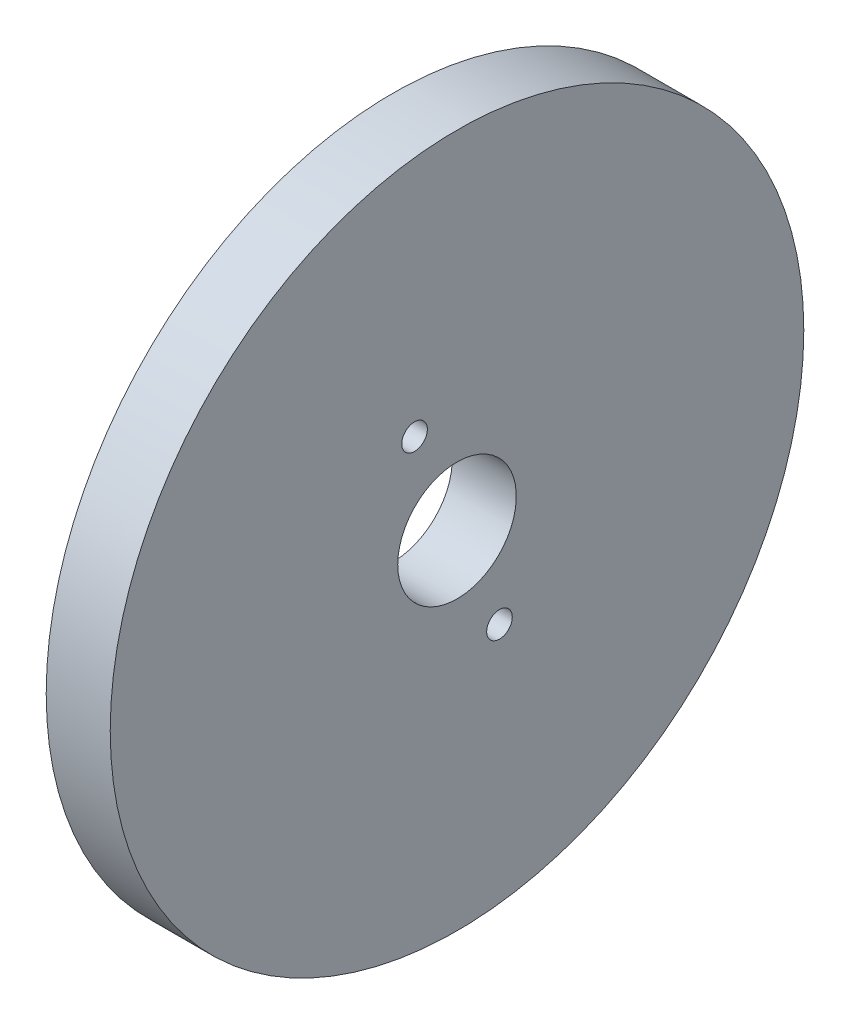
SolidWorks part; units mm, degrees
ref_plane "Front Plane" through (0, 0, 0) normal (0, 0, 1) x (1, 0, 0)
ref_plane "Top Plane" through (0, 0, 0) normal (0, 1, 0) x (1, 0, 0)
ref_plane "Right Plane" through (0, 0, 0) normal (1, 0, 0) x (0, 0, -1)
sketch "Axial profile (mm)" plane through (0, 0, 0) normal (0, 0, 1) x (1, 0, 0)
  line L0 (-110, 0) -> (75, 0) construction
  line L1 (13.7, 11.1125) -> (25.7, 11.1125)
  line L2 (25.7, 11.1125) -> (25.7, 65)
  line L3 (25.7, 65) -> (13.7, 65)
  line L4 (13.7, 65) -> (13.7, 11.1125)
revolve "Full revolution" add sketch "Axial profile (mm)" angle 360 about L0
sketch "Sketch2" plane through (0, 0, 0) normal (1, 0, 0) x (0, 0, -1)
  circle A0 centre (-7.9598, 19.2167) radius 2.4
  circle A1 centre (7.9598, -19.2167) radius 2.4
extrude "Axial holes" cut sketch "Sketch2" along normal through all and the other way through all
